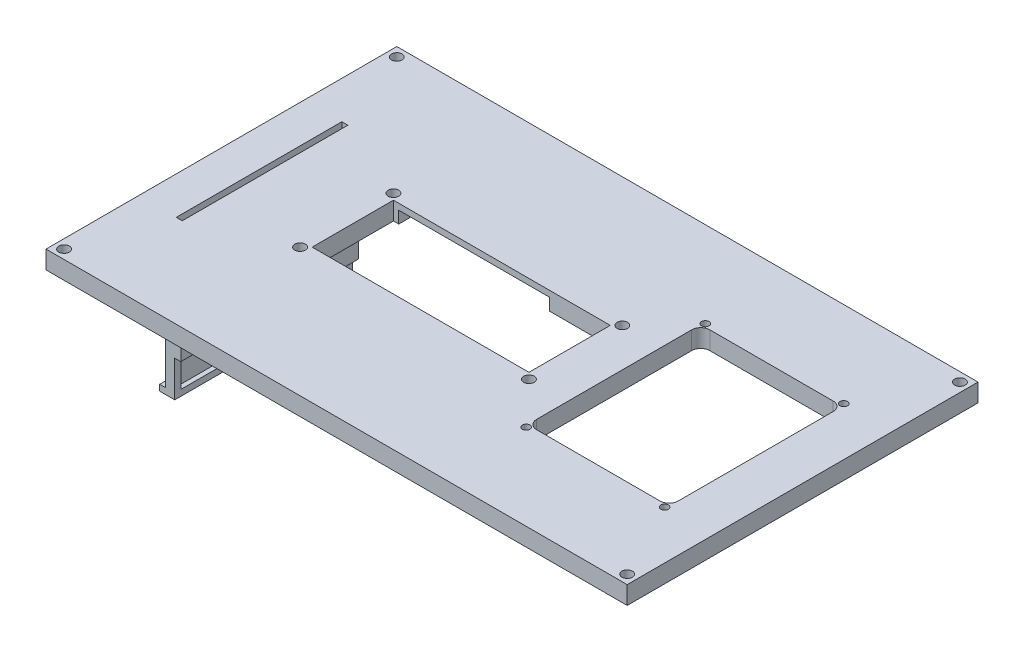
SolidWorks part; units mm, degrees
ref_plane "Front Plane" through (0, 0, 0) normal (0, 0, 1) x (1, 0, 0)
ref_plane "Top Plane" through (0, 0, 0) normal (0, 1, 0) x (1, 0, 0)
ref_plane "Right Plane" through (0, 0, 0) normal (1, 0, 0) x (0, 0, -1)
sketch "Sketch1" plane through (0, 0, 0) normal (0, 1, 0) x (1, 0, 0)
  line L1 (-73.6202, 41.1716) -> (119.3798, 41.1716)
  line L2 (-73.6202, 41.1716) -> (-73.6202, -75.3284)
  line L3 (-73.6202, -75.3284) -> (119.3798, -75.3284)
  line L4 (119.3798, 41.1716) -> (119.3798, -75.3284)
  line L5 (56.8087, 11.6716) -> (103.8087, 11.6716)
  line L6 (56.8087, 11.6716) -> (56.8087, -45.8284)
  line L7 (56.8087, -45.8284) -> (103.8087, -45.8284)
  line L8 (103.8087, 11.6716) -> (103.8087, -45.8284)
  line L9 (-29.9882, -3.5784) -> (42.0118, -3.5784)
  line L10 (-29.9882, -3.5784) -> (-29.9882, -30.5784)
  line L11 (-29.9882, -30.5784) -> (42.0118, -30.5784)
  line L12 (42.0118, -3.5784) -> (42.0118, -30.5784)
  line L13 (-48.3313, 10.4216) -> (-46.3313, 10.4216)
  line L14 (-48.3313, 10.4216) -> (-48.3313, -44.5784)
  line L15 (-48.3313, -44.5784) -> (-46.3313, -44.5784)
  line L16 (-46.3313, 10.4216) -> (-46.3313, -44.5784)
  circle A0 centre (-31.9882, -1.5784) radius 1.75
  circle A1 centre (-31.9882, -32.5784) radius 1.75
  circle A2 centre (44.0118, -1.5784) radius 1.75
  circle A3 centre (44.0118, -32.5784) radius 1.75
  circle A4 centre (-70.6202, -72.3284) radius 1.75
  circle A5 centre (-70.6202, 38.1716) radius 1.75
  circle A6 centre (116.3798, -72.3284) radius 1.75
  circle A7 centre (116.3798, 38.1716) radius 1.75
  dimension "D12" = 2
  dimension "D1" = 193
  dimension "D2" = 116.5
  dimension "D3" = 47
  dimension "D4" = 57.5
  dimension "D5" = 29.5
  dimension "D6" = 72
  dimension "D7" = 27
  dimension "D8" = 44.75
  dimension "D9" = 55
  dimension "D10" = 2
  dimension "D11" = 30.75
  dimension "D13" = 2
  dimension "D14" = 2
  dimension "D15" = 2
  dimension "D16" = 3
  dimension "D17" = 3
  dimension "D18" = 3
  dimension "D19" = 3
extrude "Boss-Extrude1" add sketch "Sketch1" along normal blind 6
sketch "Sketch3" plane through (0, 0, 0) normal (0, -1, 0) x (1, 0, 0)
  line L0 (-73.6202, 75.3284) -> (119.3798, 75.3284) construction
  line L1 (-67.6202, 69.3284) -> (-57.6202, 69.3284)
  line L2 (-67.6202, 69.3284) -> (-67.6202, 59.3284)
  line L3 (-67.6202, 59.3284) -> (-57.6202, 59.3284)
  line L4 (-57.6202, 69.3284) -> (-57.6202, 59.3284)
  line L5 (-73.6202, -41.1716) -> (-73.6202, 75.3284) construction
  line L6 (-67.6202, -25.1716) -> (-57.6202, -25.1716)
  line L7 (-67.6202, -25.1716) -> (-67.6202, -35.1716)
  line L8 (-67.6202, -35.1716) -> (-57.6202, -35.1716)
  line L9 (-57.6202, -25.1716) -> (-57.6202, -35.1716)
  line L10 (119.3798, -41.1716) -> (-73.6202, -41.1716) construction
  line L11 (103.3798, -25.1716) -> (113.3798, -25.1716)
  line L12 (103.3798, -25.1716) -> (103.3798, -35.1716)
  line L13 (103.3798, -35.1716) -> (113.3798, -35.1716)
  line L14 (113.3798, -25.1716) -> (113.3798, -35.1716)
  line L15 (119.3798, 75.3284) -> (119.3798, -41.1716) construction
  line L16 (103.3798, 69.3284) -> (113.3798, 69.3284)
  line L17 (103.3798, 69.3284) -> (103.3798, 59.3284)
  line L18 (103.3798, 59.3284) -> (113.3798, 59.3284)
  line L19 (113.3798, 69.3284) -> (113.3798, 59.3284)
  dimension "D1" = 10
  dimension "D2" = 10
  dimension "D3" = 6
  dimension "D4" = 6
  dimension "D5" = 6
  dimension "D6" = 6
  dimension "D7" = 6
  dimension "D8" = 6
  dimension "D9" = 6
  dimension "D10" = 6
  dimension "D11" = 10
  dimension "D12" = 10
  dimension "D13" = 10
  dimension "D14" = 10
  dimension "D15" = 10
  dimension "D16" = 10
extrude "Boss-Extrude3" add sketch "Sketch3" along normal blind 10
fillet "Fillet1" radius 3 4 edges at (103.8087, 3, -11.6716) (103.8087, 3, 45.8284) (56.8087, 3, -11.6716) (56.8087, 3, 45.8284)
sketch "Sketch5" plane through (0, 0, 0) normal (0, -1, 0) x (1, 0, 0)
  line L1 (-48.3313, 44.5784) -> (-46.3313, 44.5784)
  line L2 (-48.3313, 44.5784) -> (-48.3313, -10.4216)
  line L3 (-48.3313, -10.4216) -> (-46.3313, -10.4216)
  line L4 (-46.3313, 44.5784) -> (-46.3313, -10.4216)
extrude "Boss-Extrude4" add sketch "Sketch5" against normal blind 6
sketch "Sketch6" plane through (0, -10, 0) normal (0, -1, 0) x (1, 0, 0)
  line L1 (-67.6202, 69.3284) -> (113.3798, 69.3284)
  line L2 (-67.6202, 69.3284) -> (-67.6202, -35.1716)
  line L3 (-67.6202, -35.1716) -> (113.3798, -35.1716)
  line L4 (113.3798, 69.3284) -> (113.3798, -35.1716)
extrude "Cut-Extrude1" cut sketch "Sketch6" against normal blind 4
sketch "Sketch7" plane through (0, 0, 0) normal (0, -1, 0) x (1, 0, 0)
  line L0 (119.3798, -41.1716) -> (-73.6202, -41.1716) construction
  line L1 (-62.6202, 44.5784) -> (-61.1202, 44.5784)
  line L2 (-62.6202, 44.5784) -> (-62.6202, -10.4216)
  line L3 (-62.6202, -10.4216) -> (-61.1202, -10.4216)
  line L4 (-61.1202, 44.5784) -> (-61.1202, -10.4216)
  line L6 (-73.6202, -41.1716) -> (-73.6202, 75.3284) construction
  dimension "D1" = 55
  dimension "D2" = 1.5
  dimension "D3" = 30.75
  dimension "D4" = 11
extrude "Boss-Extrude5" add sketch "Sketch7" along normal blind 44.75
sketch "Sketch8" plane through (0, 0, 0) normal (0, -1, 0) x (1, 0, 0)
  line L1 (-61.1202, 44.5784) -> (-59.1202, 44.5784)
  line L2 (-61.1202, 44.5784) -> (-61.1202, -10.4216)
  line L3 (-61.1202, -10.4216) -> (-59.1202, -10.4216)
  line L4 (-59.1202, 44.5784) -> (-59.1202, -10.4216)
  dimension "D1" = 55
  dimension "D2" = 2
extrude "Cut-Extrude2" cut sketch "Sketch8" against normal blind 42.25
sketch "Sketch10" plane through (0, 0, 0) normal (0, -1, 0) x (1, 0, 0)
  line L0 (42.0118, 30.5784) -> (42.0118, 3.5784) construction
  line L1 (42.0118, 26.5784) -> (48.0118, 26.5784)
  line L2 (42.0118, 26.5784) -> (42.0118, 7.5784)
  line L3 (42.0118, 7.5784) -> (48.0118, 7.5784)
  line L4 (48.0118, 26.5784) -> (48.0118, 7.5784)
  line L5 (-73.6202, 75.3284) -> (119.3798, 75.3284) construction
  dimension "D1" = 19
  dimension "D2" = 48.75
  dimension "D3" = 6
extrude "Cut-Extrude3" cut sketch "Sketch10" against normal blind 4 contours L4 L3 L2 L1
fillet "Fillet3" radius 3 16 edges at (-62.6202, -6, -35.1716) (-67.6202, -6, -30.1716) (-62.6202, -6, -25.1716) (-57.6202, -6, -30.1716) (-67.6202, -6, 64.3284) (-62.6202, -6, 69.3284) (-57.6202, -6, 64.3284) (-62.6202, -6, 59.3284) (108.3798, -6, 69.3284) (113.3798, -6, 64.3284) (108.3798, -6, 59.3284) (103.3798, -6, 64.3284) (108.3798, -6, -25.1716) (113.3798, -6, -30.1716) (108.3798, -6, -35.1716) (103.3798, -6, -30.1716)
sketch "Sketch12" plane through (-61.1202, 0, 0) normal (1, 0, 0) x (0, 0, -1)
  line L0 (10.4216, -44.75) -> (10.4216, 0) construction
  line L1 (-44.5784, -44.75) -> (10.4216, -44.75)
  line L2 (-44.5784, -44.75) -> (-44.5784, -42.75)
  line L3 (-44.5784, -42.75) -> (10.4216, -42.75)
  line L4 (10.4216, -44.75) -> (10.4216, -42.75)
  dimension "D1" = 2
extrude "Boss-Extrude6" add sketch "Sketch12" along normal blind 1.5
sketch "Sketch14" plane through (0, 0, -10.4216) normal (0, 0, -1) x (-1, 0, 0)
  line L1 (59.6202, -44.75) -> (62.6202, -44.75)
  line L2 (59.6202, -44.75) -> (59.6202, 0)
  line L3 (59.6202, 0) -> (62.6202, 0)
  line L4 (62.6202, -44.75) -> (62.6202, 0)
  point P0 (59.6202, -44.75)
  point P1 (62.6202, 0)
extrude "Boss-Extrude7" add sketch "Sketch14" along normal blind 2
sketch "Sketch15" plane through (0, 0, 44.5784) normal (0, 0, 1) x (1, 0, 0)
  line L1 (-62.6202, 0) -> (-59.6202, 0)
  line L2 (-62.6202, 0) -> (-62.6202, -44.75)
  line L3 (-62.6202, -44.75) -> (-59.6202, -44.75)
  line L4 (-59.6202, 0) -> (-59.6202, -44.75)
  point P0 (-59.6202, -44.75)
  point P1 (-62.6202, 0)
extrude "Boss-Extrude8" add sketch "Sketch15" along normal blind 2
sketch "Sketch16" plane through (-62.6202, 0, 0) normal (-1, 0, 0) x (0, 0, 1)
  line L0 (46.5784, 0) -> (-12.4216, 0) construction
  line L2 (-10.4216, 0) -> (-10.4216, -42.75)
  line L3 (-10.4216, -42.75) -> (46.5784, -42.75)
  line L5 (46.5784, 0) -> (46.5784, -44.75) construction
  line L6 (-12.4216, -44.75) -> (-12.4216, 0) construction
  line L7 (46.5784, -44.75) -> (-12.4216, -44.75) construction
  line L8 (-10.4216, 0) -> (-12.4216, 0)
  line L9 (-12.4216, 0) -> (-12.4216, -44.75)
  line L10 (-12.4216, -44.75) -> (46.5784, -44.75)
  line L11 (46.5784, -44.75) -> (46.5784, -42.75)
  dimension "D1" = 2
  dimension "D2" = 2
extrude "Boss-Extrude9" add sketch "Sketch16" along normal blind 2 contours L2 L3 L11 L10 L9 L8
sketch "Sketch17" plane through (0, 6, 0) normal (0, 1, 0) x (1, 0, 0)
  line L0 (100.8087, 11.6716) -> (59.8087, 11.6716) construction
  line L1 (103.8087, -42.8284) -> (103.8087, 8.6716) construction
  line L2 (59.8087, -45.8284) -> (100.8087, -45.8284) construction
  line L3 (56.8087, 8.6716) -> (56.8087, -42.8284) construction
  circle A0 centre (57.3087, 12.6716) radius 1.25
  circle A1 centre (103.3087, 12.6716) radius 1.25
  circle A2 centre (57.3087, -46.8284) radius 1.25
  circle A3 centre (103.3087, -46.8284) radius 1.25
  point P2 (57.3087, 11.4216)
  point P3 (57.3087, -45.5784)
  dimension "D1" = 1
  dimension "D4" = 2.5
  dimension "D5" = 2.5
  dimension "D2" = 0.5
  dimension "D3" = 1
  dimension "D6" = 1
  dimension "D7" = 1
  dimension "D8" = 0.5
  dimension "D9" = 0.5
  dimension "D10" = 0.5
extrude "Cut-Extrude5" cut sketch "Sketch17" against normal blind 6
sketch "Sketch18" plane through (-59.6202, 0, 0) normal (1, 0, 0) x (0, 0, -1)
  line L0 (-46.5784, -44.75) -> (-46.5784, 0) construction
  line L1 (-46.5784, 0) -> (-26.5784, 0)
  line L2 (-46.5784, 0) -> (-46.5784, -32.75)
  line L3 (-46.5784, -32.75) -> (-26.5784, -32.75)
  line L4 (12.4216, 0) -> (12.4216, -32.75)
  line L5 (12.4216, 0) -> (12.4216, -44.75) construction
  line L7 (-75.3284, 0) -> (41.1716, 0) construction
  line L8 (-26.5784, -32.75) -> (-26.5784, 0)
  line L9 (-7.5784, -32.75) -> (-7.5784, 0)
  line L10 (-7.5784, -32.75) -> (12.4216, -32.75)
  line L11 (-7.5784, 0) -> (12.4216, 0)
  line L12 (-46.5784, -44.75) -> (12.4216, -44.75) construction
  dimension "D1" = 0
  dimension "D2" = 20
  dimension "D3" = 20
  dimension "D4" = 12
  dimension "D5" = 12
extrude "Boss-Extrude10" add sketch "Sketch18" along normal blind 2
sketch "Sketch19" plane through (0, 0, 0) normal (0, -1, 0) x (1, 0, 0)
  line L0 (-29.9882, 30.5784) -> (42.0118, 30.5784) construction
  line L1 (-28.2382, 35.5784) -> (21.7618, 35.5784)
  line L2 (-28.2382, 35.5784) -> (-28.2382, -1.4216)
  line L3 (-28.2382, -1.4216) -> (21.7618, -1.4216)
  line L4 (21.7618, 35.5784) -> (21.7618, -1.4216)
  line L5 (42.0118, 3.5784) -> (-29.9882, 3.5784) construction
  circle A0 centre (-31.9882, 32.5784) radius 1.75 construction
  point P8 (-30.2382, 32.5784)
  dimension "D1" = 50
  dimension "D2" = 5
  dimension "D3" = 5
  dimension "D4" = 2
extrude "Cut-Extrude7" cut sketch "Sketch19" against normal blind 4
